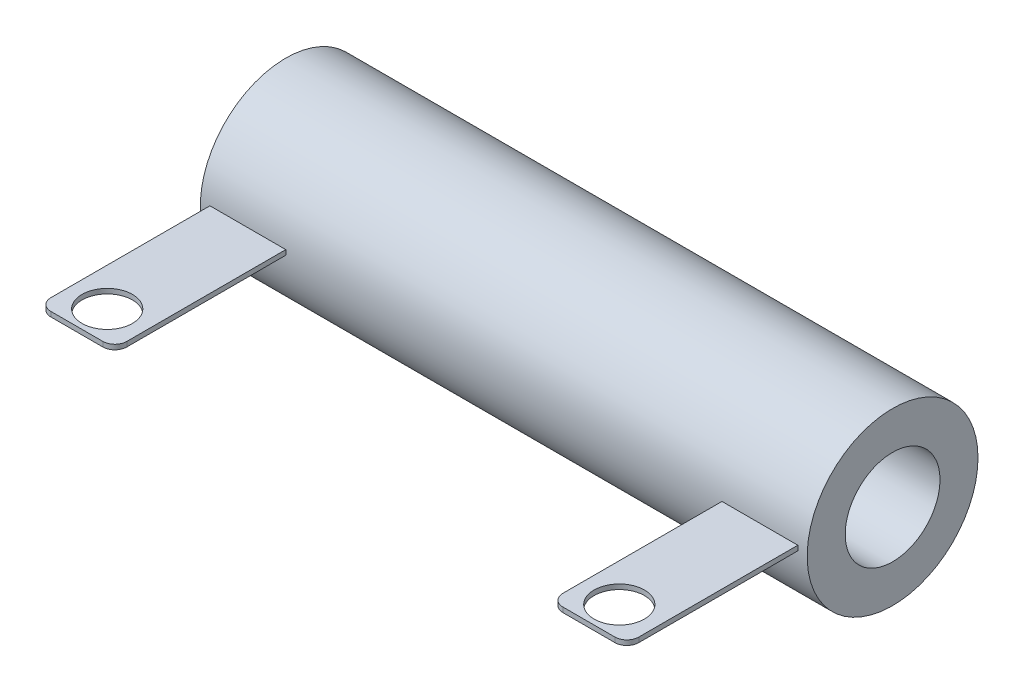
SolidWorks part; units mm, degrees
ref_plane "Front Plane" through (0, 0, 0) normal (0, 0, 1) x (1, 0, 0)
ref_plane "Top Plane" through (0, 0, 0) normal (0, 1, 0) x (1, 0, 0)
ref_plane "Right Plane" through (0, 0, 0) normal (1, 0, 0) x (0, 0, -1)
sketch "Sketch1" plane through (0, 0, 0) normal (1, 0, 0) x (0, 0, -1)
  circle A0 centre (0, 0) radius 3.97
  circle A1 centre (0, 0) radius 7.15
  dimension "D1" = 7.94
  dimension "D2" = 14.3
extrude "Boss-Extrude1" add sketch "Sketch1" along normal mid plane 50.8
sketch "Sketch2" plane through (0, 0, 0) normal (0, 1, 0) x (1, 0, 0)
  line L0 (-25.4, -7.15) -> (25.4, -7.15) construction
  line L1 (-24.606, -5.194) -> (-18.256, -5.194)
  line L2 (-24.606, -5.194) -> (-24.606, -20.45)
  line L3 (-23.606, -21.45) -> (-19.256, -21.45)
  line L4 (-18.256, -5.194) -> (-18.256, -20.45)
  line L6 (-25.4, 7.15) -> (-25.4, -7.15) construction
  line L7 (0, 10.768) -> (0, -16.9806) construction
  line L8 (18.256, -5.194) -> (18.256, -20.45)
  line L9 (23.606, -21.45) -> (19.256, -21.45)
  line L10 (24.606, -5.194) -> (24.606, -20.45)
  line L11 (24.606, -5.194) -> (18.256, -5.194)
  circle A0 centre (-21.431, -18.91) radius 2.1085
  arc A1 (-19.256, -21.45) -> (-18.256, -20.45) centre (-19.256, -20.45) ccw
  arc A2 (-24.606, -20.45) -> (-23.606, -21.45) centre (-23.606, -20.45) ccw
  arc A3 (24.606, -20.45) -> (23.606, -21.45) centre (23.606, -20.45) cw
  arc A4 (19.256, -21.45) -> (18.256, -20.45) centre (19.256, -20.45) cw
  circle A5 centre (21.431, -18.91) radius 2.1085
  point P10 (-21.431, -21.45)
  point P18 (-18.256, -21.45)
  point P21 (-24.606, -21.45)
  point P32 (24.606, -21.45)
  point P33 (18.256, -21.45)
  point P34 (21.431, -21.45)
  dimension "D4" = 4.217
  dimension "D7" = 1
  dimension "D1" = 6.35
  dimension "D2" = 6.35
  dimension "D3" = 14.3
  dimension "D5" = 0.794
  dimension "D6" = 2.54
extrude "Boss-Extrude2" add sketch "Sketch2" along normal blind 0.407 separate body
